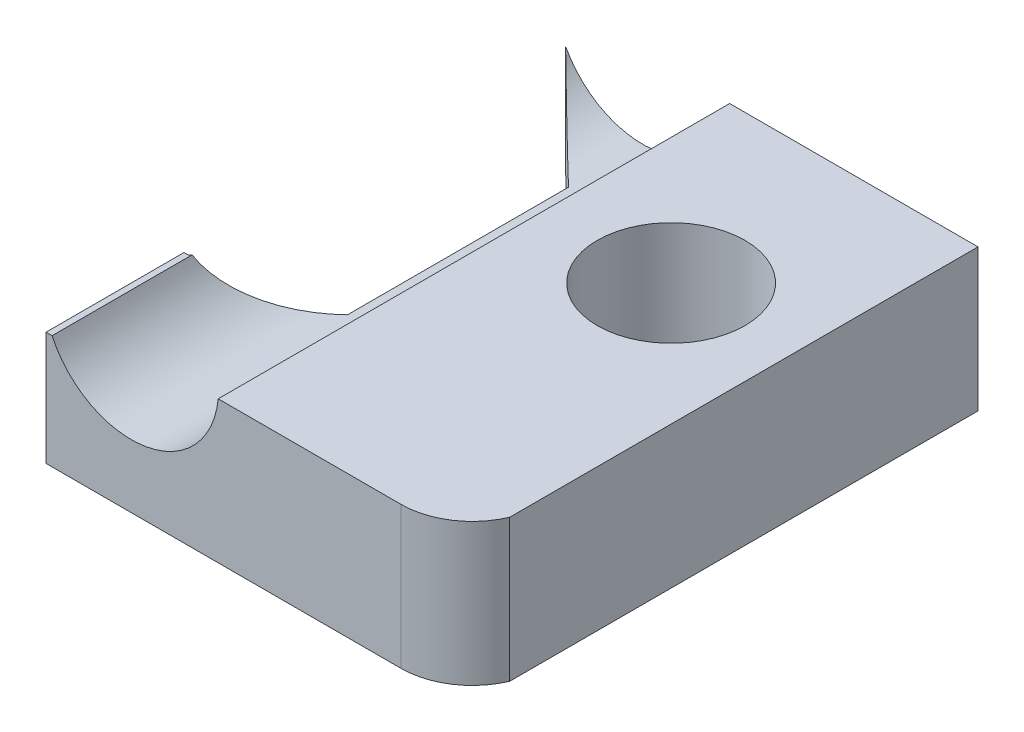
SolidWorks part; units mm, degrees
ref_plane "Front Plane" through (0, 0, 0) normal (0, 0, 1) x (1, 0, 0)
ref_plane "Top Plane" through (0, 0, 0) normal (0, 1, 0) x (1, 0, 0)
ref_plane "Right Plane" through (0, 0, 0) normal (1, 0, 0) x (0, 0, -1)
sketch "Sketch1" plane through (0, 0, 0) normal (0, 1, 0) x (1, 0, 0)
  line L0 (0, 18) -> (2.8, 15.3041)
  line L1 (0, 0) -> (15, 0)
  line L2 (0, 0) -> (0, 5)
  line L3 (0, 18) -> (15, 18)
  line L4 (15, 0) -> (15, 18)
  line L5 (2.8, 15.3041) -> (2.8, 7.6956)
  line L6 (2.8, 7.6956) -> (0, 5)
  line L7 (0, 5) -> (0, 18) construction
  circle A0 centre (10.5, 11.4995) radius 2.6
  dimension "D3" = 5.2
  dimension "D1" = 18
  dimension "D2" = 15
  dimension "D4" = 2.8
  dimension "D5" = 4.5
  dimension "D6" = 13
extrude "Boss-Extrude1" add sketch "Sketch1" along normal blind 5 and the other way blind 0.0001
sketch "Sketch2" plane through (0, 0, 0) normal (0, 0, 1) x (1, 0, 0)
  line L0 (0, 3.4999) -> (0.507, 3.4999)
  line L1 (0, -0.0001) -> (0, 5) construction
  line L2 (0, -0.0001) -> (15, -0.0001) construction
  line L4 (0, -0.0001) -> (0, 5)
  circle A0 centre (3, 5.3) radius 3.075
  line M4 (15, 5) -> (0, 5)
  dimension "D1" = 3.5
  dimension "D2" = 6.15
  dimension "D3" = 5.3001
  dimension "D4" = 3
extrude "Cut-Extrude1" cut sketch "Sketch2" against normal through all contours A0 M4
fillet "Fillet1" radius 2.5 1 edges at (15, 2.5, 0)
sketch "Sketch3" plane through (0, 0, 0) normal (0, 0, 1) x (1, 0, 0)
  line L0 (6.0603, 5) -> (12.5, 5) construction
  line L1 (0, 5) -> (0.7173, 5)
  line L2 (0, 5) -> (0, 4)
  line L3 (0, 4) -> (0.7173, 4)
  line L4 (0.7173, 5) -> (0.7173, 4)
  dimension "D1" = 1
extrude "Cut-Extrude2" cut sketch "Sketch3" against normal through all
sketch "Sketch4" plane through (0, -0.0001, 0) normal (0, -1, 0) x (1, 0, 0)
  line L6 (0.1387, -4.8559) -> (-0.9036, -4.8559)
  line L7 (-0.9036, -4.8559) -> (-0.9036, -18.1441)
  line L8 (-0.9036, -18.1441) -> (0.1387, -18.1441)
  line L9 (0.1387, -18.1441) -> (3, -15.3891)
  line L10 (3, -15.3891) -> (3, -7.6106)
  line L11 (3, -7.6106) -> (0.1387, -4.8559)
  line L12 (0.1387, -18.1441) -> (3, -15.3891)
  line L13 (3, -15.3891) -> (3, -7.6106)
  line L14 (3, -7.6106) -> (0.1387, -4.8559)
  line L16 (15, -18) -> (14.8, -18)
  line L17 (15, -18) -> (15, 0)
  line L18 (15, 0) -> (14.8, 0)
  line L19 (14.8, -18) -> (14.8, 0)
  dimension "D2" = 0.2
  dimension "D1" = 0.2
extrude "Cut-Extrude3" cut sketch "Sketch4" against normal through all
